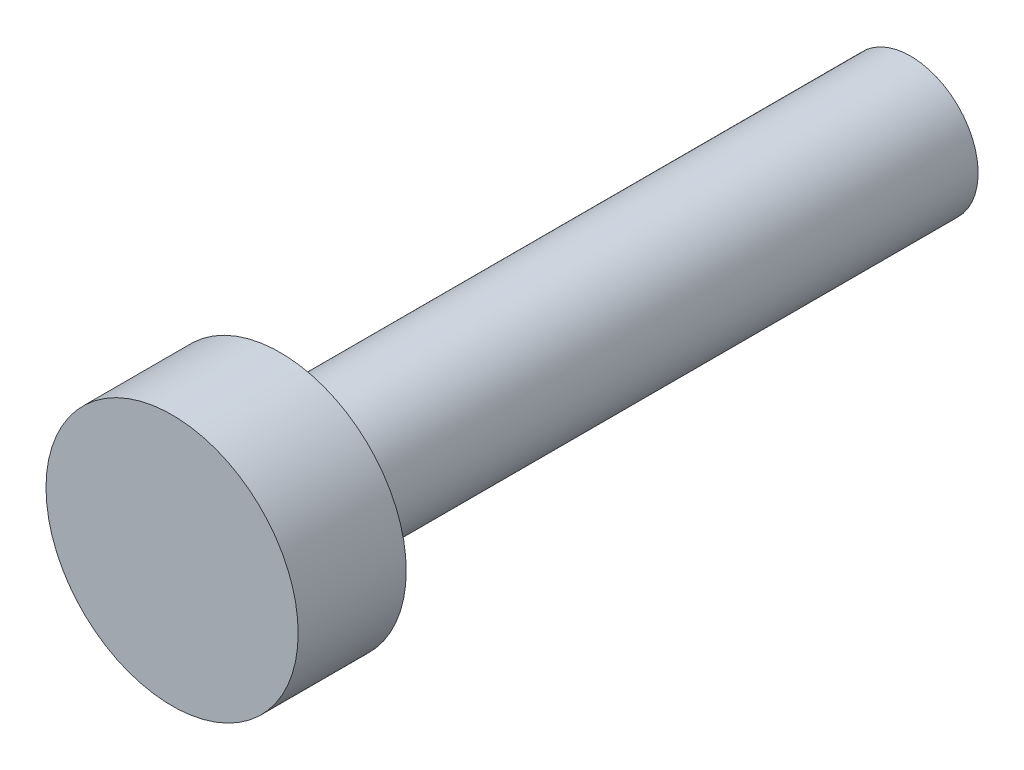
SolidWorks part; units mm, degrees
ref_plane "Plan de face" through (0, 0, 0) normal (0, 0, 1) x (1, 0, 0)
ref_plane "Plan de dessus" through (0, 0, 0) normal (0, 1, 0) x (1, 0, 0)
ref_plane "Plan de droite" through (0, 0, 0) normal (1, 0, 0) x (0, 0, -1)
sketch "Esquisse1" plane through (0, 0, 0) normal (0, 0, 1) x (1, 0, 0)
  circle A0 centre (0, 0) radius 2.8
  dimension "D1" = 5.6
extrude "Boss.-Extru.1" add sketch "Esquisse1" along normal blind 2.4
sketch "Esquisse2" plane through (0, 0, 0) normal (0, 0, -1) x (-1, 0, 0)
  circle A0 centre (0, 0) radius 1.5
  dimension "D1" = 3
extrude "Boss.-Extru.2" add sketch "Esquisse2" along normal blind 14
